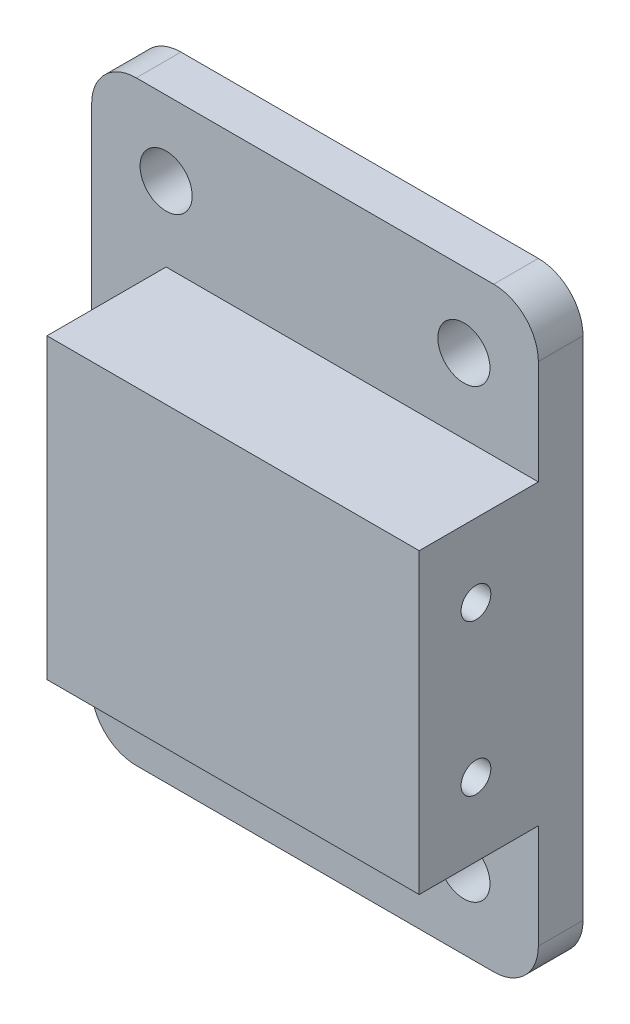
SolidWorks part; units mm, degrees
ref_plane "前基準面" through (0, 0, 0) normal (0, 0, 1) x (1, 0, 0)
ref_plane "上基準面" through (0, 0, 0) normal (0, 1, 0) x (1, 0, 0)
ref_plane "右基準面" through (0, 0, 0) normal (1, 0, 0) x (0, 0, -1)
sketch "草圖1" plane through (0, 0, 0) normal (0, 0, 1) x (1, 0, 0)
  line L1 (-15, -20) -> (15, -20)
  line L2 (-15, -20) -> (-15, 20)
  line L3 (-15, 20) -> (15, 20)
  line L4 (15, -20) -> (15, 20)
  line L5 (-15, -20) -> (15, 20) construction
  line L6 (-15, 20) -> (15, -20) construction
  point P0 (0, 0)
  dimension "D1" = 40
  dimension "D2" = 30
extrude "填料-伸長1" add sketch "草圖1" along normal mid plane 3
sketch "草圖2" plane through (0, 0, 1.5) normal (0, 0, 1) x (1, 0, 0)
  line L0 (15, -20) -> (15, 20) construction
  line L1 (-10, -10) -> (15, -10)
  line L2 (-10, -10) -> (-10, 10)
  line L3 (-10, 10) -> (15, 10)
  line L4 (15, -10) -> (15, 10)
  point P0 (-10, 0)
  point P8 (0, 0)
  dimension "D1" = 20
  dimension "D2" = 25
extrude "填料-伸長2" add sketch "草圖2" along normal blind 8
hole_wizard "Ø2.0 (2) 直徑孔3" positions "草圖4" profile "草圖5" hole size "Ø2.0" standard "ISO" end condition through all
sketch "草圖4" plane through (-10, 0, 0) normal (-1, 0, 0) x (0, 0, 1)
  line L0 (5.69, 5.08) -> (5.69, -5.08)
  line L2 (1.5, 20) -> (1.5, -20) construction
  point P1 (5.69, 5.08)
  point P2 (5.69, -5.08)
  point P12 (5.69, 0)
  point P24 (0, 0)
  dimension "D1" = 10.16
  dimension "D2" = 4.19
sketch "草圖5" plane through (-10, 5.08, 5.69) normal (0, 1, 0) x (0, 0, 1)
  line L0 (0, 0) -> (0, 25)
  line L1 (0, 25) -> (1, 25)
  line L2 (1, 25) -> (1, 0)
  line L5 (1, 0) -> (0, 0)
  line L11 (0, -6.35) -> (0, 107.95) construction
  dimension "貫穿孔直徑" = 2
  dimension "貫穿孔深度" = 25
hole_wizard "Ø3.5 (3.5) 直徑孔1" positions "草圖11" profile "草圖10" hole size "Ø3.5" standard "ISO" end condition through all
sketch "草圖11" plane through (0, 0, 1.5) normal (0, 0, 1) x (1, 0, 0)
  line L1 (-10, -15) -> (10, -15)
  line L2 (-10, -15) -> (-10, 15)
  line L3 (-10, 15) -> (10, 15)
  line L4 (10, -15) -> (10, 15)
  line L5 (-10, -15) -> (10, 15) construction
  line L6 (-10, 15) -> (10, -15) construction
  point P12 (10, 15)
  point P115 (-10, -15)
  point P116 (-10, 15)
  point P117 (10, -15)
  dimension "D1" = 20
  dimension "D2" = 30
sketch "草圖10" plane through (10, 15, 1.5) normal (1, 0, 0) x (0, -1, 0)
  line L0 (0, 0) -> (0, 3)
  line L1 (0, 3) -> (1.75, 3)
  line L2 (1.75, 3) -> (1.75, 0)
  line L5 (1.75, 0) -> (0, 0)
  line L11 (0, -6.35) -> (0, 107.95) construction
  dimension "貫穿孔直徑" = 3.5
  dimension "貫穿孔深度" = 3
fillet "圓角1" radius 3 4 edges at (15, 20, 0) (-15, 20, 0) (15, -20, 0) (-15, -20, 0)
